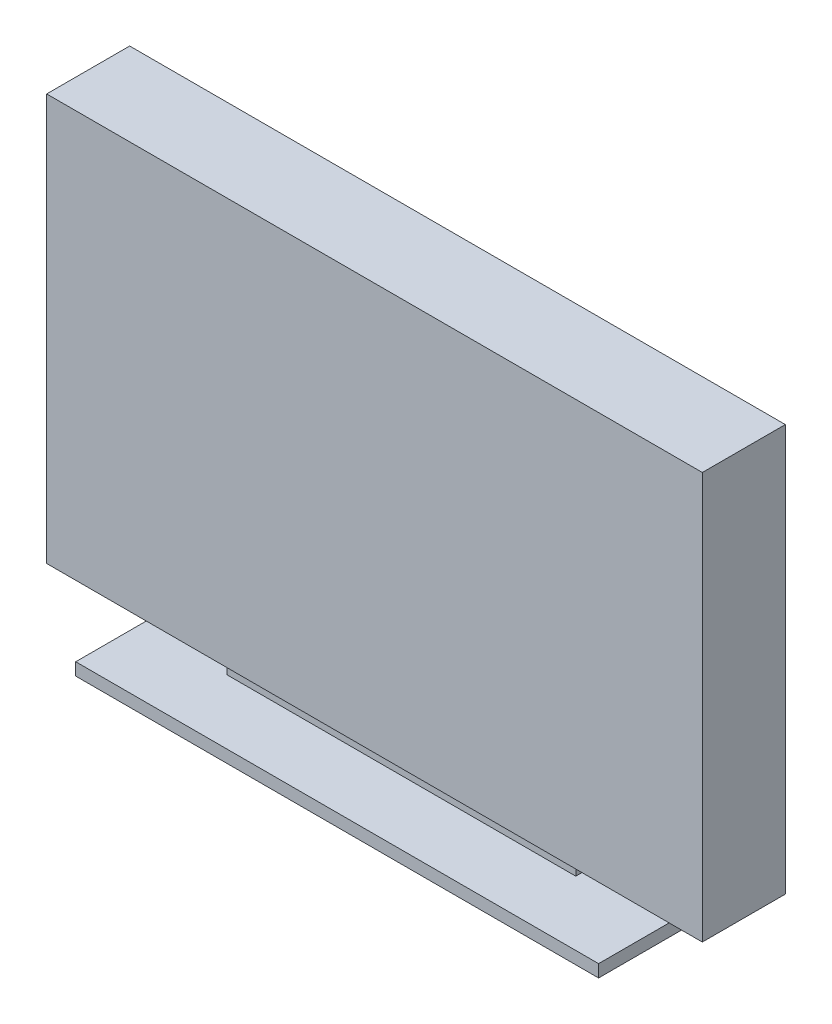
SolidWorks part; units mm, degrees
ref_plane "Front Plane" through (0, 0, 0) normal (0, 0, 1) x (1, 0, 0)
ref_plane "Top Plane" through (0, 0, 0) normal (0, 1, 0) x (1, 0, 0)
ref_plane "Right Plane" through (0, 0, 0) normal (1, 0, 0) x (0, 0, -1)
sketch "Sketch1" plane through (0, 0, 0) normal (0, 1, 0) x (1, 0, 0)
  line L1 (-315, -95) -> (315, -95)
  line L2 (-315, -95) -> (-315, 95)
  line L3 (-315, 95) -> (315, 95)
  line L4 (315, -95) -> (315, 95)
  line L5 (-315, -95) -> (315, 95) construction
  line L6 (-315, 95) -> (315, -95) construction
  point P0 (0, 0)
  dimension "D1" = 630
  dimension "D2" = 190
extrude "Boss-Extrude1" add sketch "Sketch1" along normal blind 15
sketch "Sketch3" plane through (0, 15, 0) normal (0, 1, 0) x (1, 0, 0)
  line L1 (-210, -17.5) -> (210, -17.5)
  line L2 (-210, -17.5) -> (-210, 17.5)
  line L3 (-210, 17.5) -> (210, 17.5)
  line L4 (210, -17.5) -> (210, 17.5)
  line L5 (-210, -17.5) -> (210, 17.5) construction
  line L6 (-210, 17.5) -> (210, -17.5) construction
  point P0 (0, 0)
  dimension "D1" = 420
  dimension "D2" = 35
extrude "Boss-Extrude2" add sketch "Sketch3" along normal blind 40
sketch "Sketch4" plane through (0, 55, 0) normal (0, 1, 0) x (1, 0, 0)
  line L1 (-395, -50) -> (395, -50)
  line L2 (-395, -50) -> (-395, 50)
  line L3 (-395, 50) -> (395, 50)
  line L4 (395, -50) -> (395, 50)
  line L5 (-395, -50) -> (395, 50) construction
  line L6 (-395, 50) -> (395, -50) construction
  point P0 (0, 0)
  dimension "D1" = 790
  dimension "D2" = 100
extrude "Boss-Extrude3" add sketch "Sketch4" along normal blind 490
